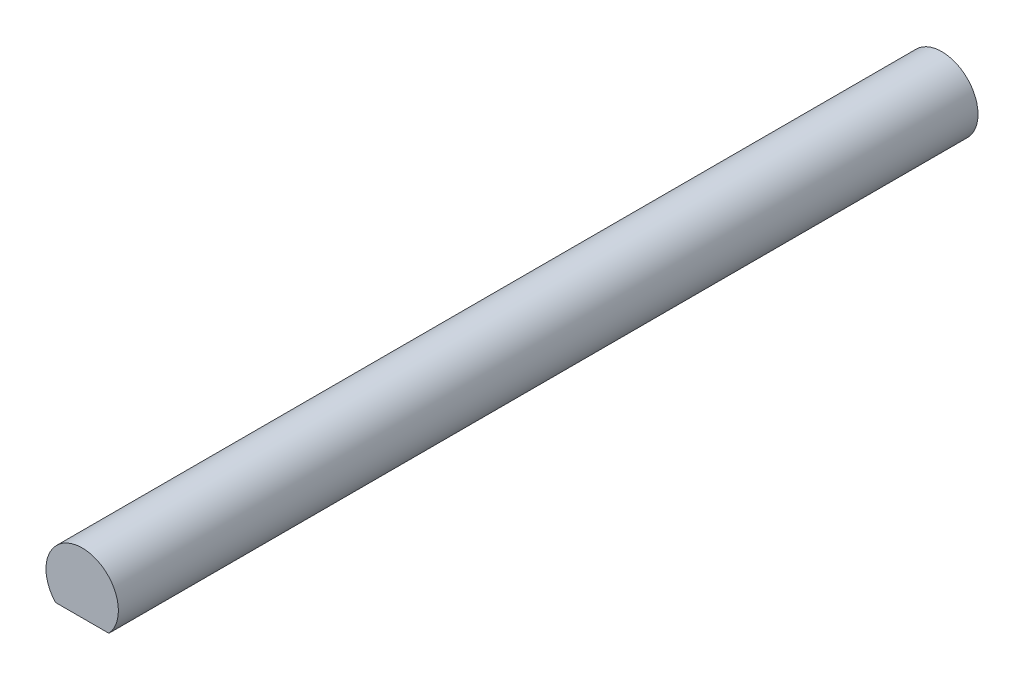
SolidWorks part; units mm, degrees
ref_plane "Ebene vorne" through (0, 0, 0) normal (0, 0, 1) x (1, 0, 0)
ref_plane "Ebene oben" through (0, 0, 0) normal (0, 1, 0) x (1, 0, 0)
ref_plane "Ebene rechts" through (0, 0, 0) normal (1, 0, 0) x (0, 0, -1)
sketch "Skizze1" plane through (0, 0, 0) normal (0, 0, 1) x (1, 0, 0)
  line L0 (0, 0) -> (-24580.393, 0) construction
  line L1 (-2.9513, -2.7) -> (2.9513, -2.7)
  arc A0 (2.9513, -2.7) -> (-2.9513, -2.7) centre (0, 0) ccw
  dimension "D1" = 8
  dimension "D2" = 6.7
extrude "Aufsatz-Linear austragen1" add sketch "Skizze1" along normal mid plane 95
